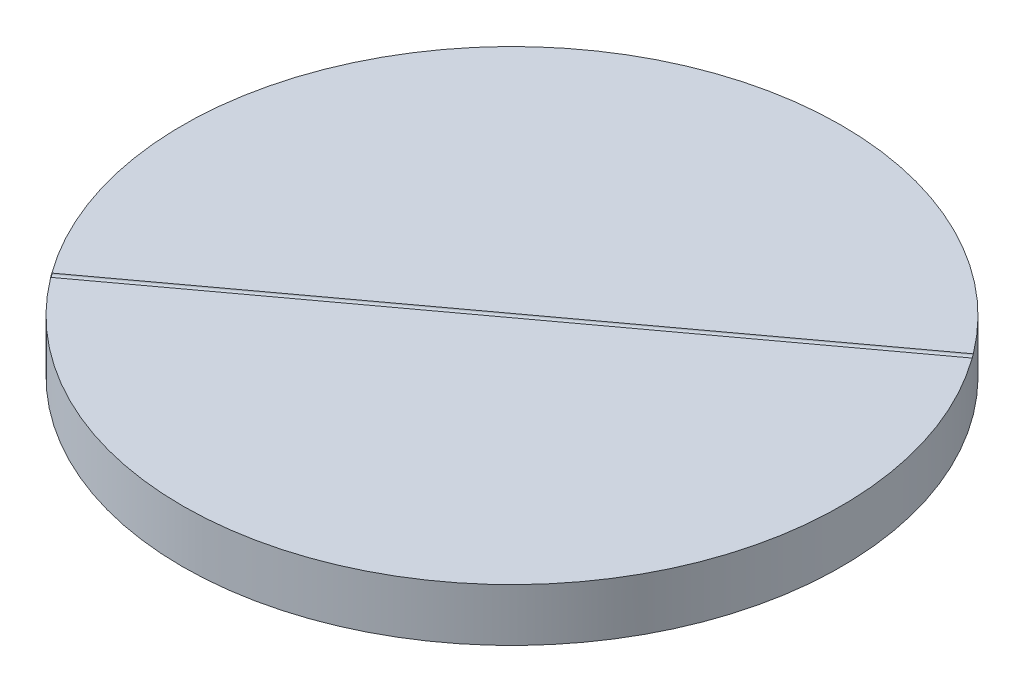
SolidWorks part; units mm, degrees
material "Acrylic (Medium-high impact)"
ref_plane "Front Plane" through (0, 0, 0) normal (0, 0, 1) x (1, 0, 0)
ref_plane "Top Plane" through (0, 0, 0) normal (0, 1, 0) x (1, 0, 0)
ref_plane "Right Plane" through (0, 0, 0) normal (1, 0, 0) x (0, 0, -1)
sketch "Sketch1" plane through (0, 0, 0) normal (0, 1, 0) x (1, 0, 0)
  circle A0 centre (0, 0) radius 3.175
  dimension "D1" = 6.35
extrude "Boss-Extrude1" add sketch "Sketch1" along normal blind 0.508
sketch "Sketch2" plane through (0, 0.508, 0) normal (0, 1, 0) x (1, 0, 0)
  line L0 (-2.5565, -1.8828) -> (2.5565, 1.8828)
  line L1 (-2.5413, -1.9032) -> (2.5715, 1.8623)
  line L2 (2.5715, 1.8623) -> (2.5565, 1.8828)
  line L3 (-2.5413, -1.9032) -> (-2.5565, -1.8828)
  circle A0 centre (0, 0) radius 3.175 construction
  dimension "D1" = 0.0254
revolve "Cut-Revolve1" cut sketch "Sketch2" angle 180 about L0
